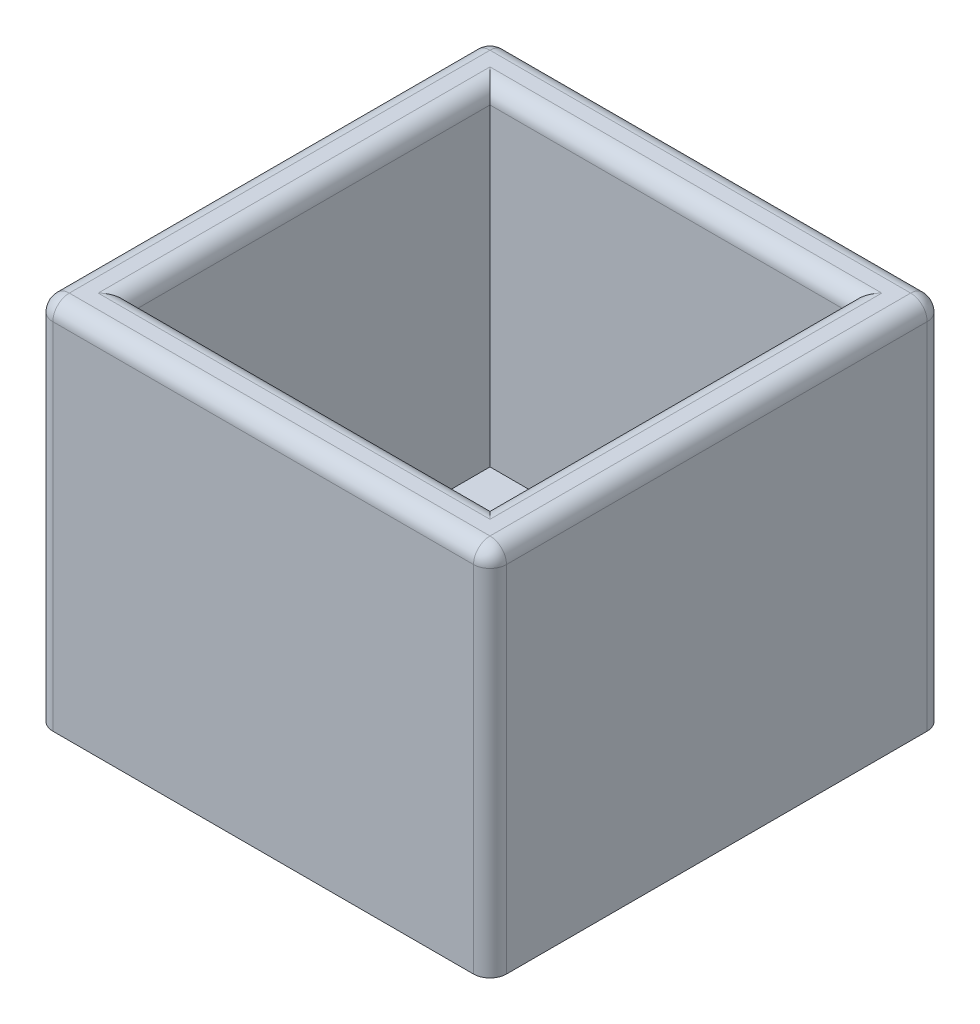
SolidWorks part; units mm, degrees
ref_plane "Front Plane" through (0, 0, 0) normal (0, 0, 1) x (1, 0, 0)
ref_plane "Top Plane" through (0, 0, 0) normal (0, 1, 0) x (1, 0, 0)
ref_plane "Right Plane" through (0, 0, 0) normal (1, 0, 0) x (0, 0, -1)
sketch "Sketch1" plane through (0, 0, 0) normal (0, 0, 1) x (1, 0, 0)
  line L1 (-27.5, 22.5) -> (27.5, 22.5)
  line L2 (-27.5, 22.5) -> (-27.5, -22.5)
  line L3 (-27.5, -22.5) -> (27.5, -22.5)
  line L4 (27.5, 22.5) -> (27.5, -22.5)
  line L5 (-27.5, 22.5) -> (27.5, -22.5) construction
  line L6 (-27.5, -22.5) -> (27.5, 22.5) construction
  point P0 (0, 0)
extrude "Boss-Extrude1" add sketch "Sketch1" along normal blind 55
sketch "Sketch2" plane through (0, 22.5, 0) normal (0, 1, 0) x (1, 0, 0)
  line L0 (-21.75, -27.5) -> (21.75, -27.5) construction
  line L1 (-21.75, -5.75) -> (21.75, -5.75)
  line L2 (-21.75, -5.75) -> (-21.75, -49.25)
  line L3 (-21.75, -49.25) -> (21.75, -49.25)
  line L4 (21.75, -5.75) -> (21.75, -49.25)
  line L5 (0, -49.25) -> (0, -5.75) construction
  line L7 (27.5, -55) -> (-27.5, -55) construction
  dimension "D1" = 43.5
  dimension "D2" = 43.5
extrude "Cut-Extrude1" cut sketch "Sketch2" against normal blind 40
fillet "Fillet2" radius 2 12 edges at (-27.5, 0, 0) (-27.5, 22.5, 27.5) (0, 22.5, 0) (27.5, 0, 0) (27.5, 22.5, 27.5) (27.5, 0, 55) (0, 22.5, 55) (-27.5, 0, 55) (-21.75, 22.5, 27.5) (0, 22.5, 49.25) (0, 22.5, 5.75) (21.75, 22.5, 27.5)
